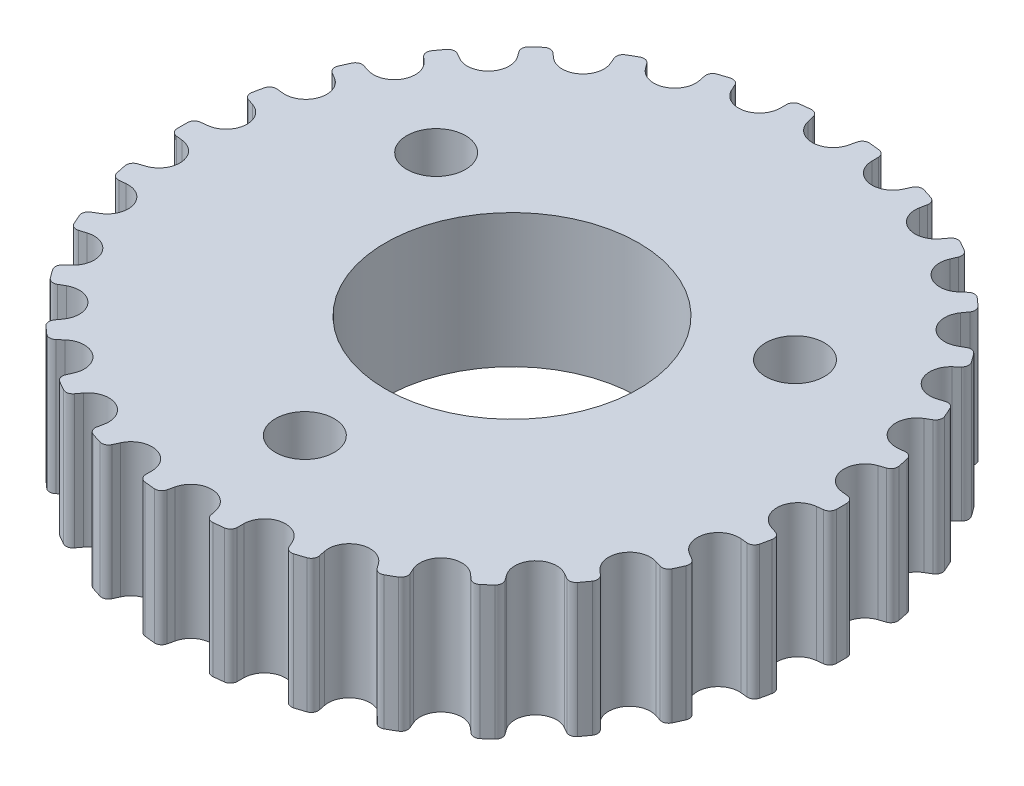
SolidWorks part; units mm, degrees
ref_plane "Front Plane" through (0, 0, 0) normal (0, 0, 1) x (1, 0, 0)
ref_plane "Top Plane" through (0, 0, 0) normal (0, 1, 0) x (1, 0, 0)
ref_plane "Right Plane" through (0, 0, 0) normal (1, 0, 0) x (0, 0, -1)
sketch "Sketch1" plane through (0, 0, 0) normal (0, 1, 0) x (1, 0, 0)
  circle A0 centre (0, 0) radius 14.3239
  dimension "D1" = 28.6479
extrude "Boss-Extrude1" add sketch "Sketch1" along normal blind 5.8
sketch "Sketch2" plane through (0, 5.8, 0) normal (0, 1, 0) x (1, 0, 0)
  line L0 (0, 0) -> (0, 14.3239) construction
  line L1 (-0.8883, 13.7564) -> (-0.95, 14.0339)
  line L2 (-2.9781, 14.0109) -> (-2.9781, 14.3239)
  line L3 (-2.9781, 14.3239) -> (2.9781, 14.3239)
  line L4 (0.8883, 13.7564) -> (0.95, 14.0339)
  line L5 (2.9781, 14.0109) -> (2.9781, 14.3239)
  circle A0 centre (0, 0) radius 14.3239 construction
  arc A1 (0.8883, 13.7564) -> (-0.8883, 13.7564) centre (0, 13.9539) cw
  arc A2 (-0.95, 14.0339) -> (-1.2694, 14.2676) centre (-1.2428, 13.9688) ccw
  arc A4 (0.95, 14.0339) -> (1.2694, 14.2676) centre (1.2428, 13.9688) cw
  arc A5 (-1.2694, 14.2676) -> (-2.9781, 14.0109) centre (0, 0) ccw
  arc A6 (1.2694, 14.2676) -> (2.9781, 14.0109) centre (0, 0) cw
  circle A8 centre (0, 0) radius 14.3239 construction
  point P11 (0, 14.3239)
  point P19 (0, 13.0439)
  dimension "D3" = 0.3
  dimension "D5" = 0.91
  dimension "D2" = 0.95
  dimension "D4" = 1.28
  dimension "D6" = 12
extrude "Cut-Extrude1" cut sketch "Sketch2" against normal through all
pattern_circular "CirPattern1" count 30 over 360 about axis through (0, 0, 0) along (0, 1, 0) of "Cut-Extrude1"
sketch "Sketch3" plane through (0, 0, 0) normal (0, -1, 0) x (1, 0, 0)
  circle A0 centre (0, 0) radius 5.5
  dimension "D1" = 11
extrude "Cut-Extrude2" cut sketch "Sketch3" against normal through all
sketch "Sketch4" plane through (0, 0, 0) normal (0, -1, 0) x (1, 0, 0)
  line L0 (0, 0) -> (0, 9) construction
  circle A0 centre (0, 9) radius 1.275
  circle A1 centre (7.7942, -4.5) radius 1.275
  circle A2 centre (-7.7942, -4.5) radius 1.275
  point P14 (0, 0)
  dimension "D1" = 2.55
  dimension "D2" = 9
  dimension "D3" = 3
extrude "Cut-Extrude3" cut sketch "Sketch4" against normal through all
sketch "Sketch5" plane through (0, 0, 0) normal (0, -1, 0) x (1, 0, 0)
  line L60 (8.7383, -10.682) -> (8.9513, -10.8702)
  line L61 (8.7383, -10.682) -> (8.9513, -10.8702)
  line L62 (9.875, -10.0385) -> (9.7101, -9.807)
  line L63 (9.875, -10.0385) -> (9.7101, -9.807)
  line L64 (12.5987, 6.2896) -> (12.3276, 6.2043)
  line L65 (12.5987, 6.2896) -> (12.3276, 6.2043)
  line L66 (11.5369, 7.5738) -> (11.7463, 7.766)
  line L67 (11.5369, 7.5738) -> (11.7463, 7.766)
  line L68 (-3.638, 13.3126) -> (-3.7561, 13.5712)
  line L69 (-3.638, 13.3126) -> (-3.7561, 13.5712)
  line L70 (-4.9382, 13.1871) -> (-4.8817, 12.9085)
  line L71 (-4.9382, 13.1871) -> (-4.8817, 12.9085)
  line L72 (-11.7463, 7.766) -> (-11.5369, 7.5738)
  line L73 (-11.7463, 7.766) -> (-11.5369, 7.5738)
  line L74 (-12.3276, 6.2043) -> (-12.5987, 6.2896)
  line L75 (-12.3276, 6.2043) -> (-12.5987, 6.2896)
  line L76 (-13.1043, 5.1541) -> (-12.8594, 5.0097)
  line L77 (-13.1043, 5.1541) -> (-12.8594, 5.0097)
  line L78 (-13.3481, 3.5057) -> (-13.6311, 3.5327)
  line L79 (-13.3481, 3.5057) -> (-13.6311, 3.5327)
  line L80 (-13.8895, 2.3169) -> (-13.62, 2.2266)
  line L81 (-13.8895, 2.3169) -> (-13.62, 2.2266)
  line L82 (-13.7853, 0.6538) -> (-14.0677, 0.6215)
  line L83 (-13.7853, 0.6538) -> (-14.0677, 0.6215)
  line L84 (-14.0677, -0.6215) -> (-13.7853, -0.6538)
  line L85 (-14.0677, -0.6215) -> (-13.7853, -0.6538)
  line L86 (-13.62, -2.2266) -> (-13.8895, -2.3169)
  line L87 (-13.62, -2.2266) -> (-13.8895, -2.3169)
  line L88 (-13.6311, -3.5327) -> (-13.3481, -3.5057)
  line L89 (-13.6311, -3.5327) -> (-13.3481, -3.5057)
  line L90 (-12.8594, -5.0097) -> (-13.1043, -5.1541)
  line L91 (-12.8594, -5.0097) -> (-13.1043, -5.1541)
  line L92 (-12.5987, -6.2896) -> (-12.3276, -6.2043)
  line L93 (-12.5987, -6.2896) -> (-12.3276, -6.2043)
  line L94 (-11.5369, -7.5738) -> (-11.7463, -7.766)
  line L95 (-11.5369, -7.5738) -> (-11.7463, -7.766)
  line L96 (-11.0157, -8.7716) -> (-10.7682, -8.6318)
  line L97 (-11.0157, -8.7716) -> (-10.7682, -8.6318)
  line L98 (-9.7101, -9.807) -> (-9.875, -10.0385)
  line L99 (-9.7101, -9.807) -> (-9.875, -10.0385)
  line L100 (-8.9513, -10.8702) -> (-8.7383, -10.682)
  line L101 (-8.9513, -10.8702) -> (-8.7383, -10.682)
  line L102 (-7.4589, -11.6115) -> (-7.5721, -11.8722)
  line L103 (-7.4589, -11.6115) -> (-7.5721, -11.8722)
  line L104 (-6.4956, -12.4937) -> (-6.3264, -12.2653)
  line L105 (-6.4956, -12.4937) -> (-6.3264, -12.2653)
  line L106 (-4.8817, -12.9085) -> (-4.9382, -13.1871)
  line L107 (-4.8817, -12.9085) -> (-4.9382, -13.1871)
  line L108 (-3.7561, -13.5712) -> (-3.638, -13.3126)
  line L109 (-3.7561, -13.5712) -> (-3.638, -13.3126)
  line L110 (-2.0912, -13.6414) -> (-2.0886, -13.9257)
  line L111 (-2.0912, -13.6414) -> (-2.0886, -13.9257)
  line L120 (6.3264, -12.2653) -> (6.4956, -12.4937)
  line L121 (7.5721, -11.8722) -> (7.4589, -11.6115)
  line L124 (10.7682, -8.6318) -> (11.0157, -8.7716)
  line L125 (11.7463, -7.766) -> (11.5369, -7.5738)
  line L126 (12.3276, -6.2043) -> (12.5987, -6.2896)
  line L127 (13.1043, -5.1541) -> (12.8594, -5.0097)
  line L128 (13.3481, -3.5057) -> (13.6311, -3.5327)
  line L129 (13.8895, -2.3169) -> (13.62, -2.2266)
  line L130 (13.7853, -0.6538) -> (14.0677, -0.6215)
  line L131 (14.0677, 0.6215) -> (13.7853, 0.6538)
  line L132 (13.62, 2.2266) -> (13.8895, 2.3169)
  line L133 (13.6311, 3.5327) -> (13.3481, 3.5057)
  line L134 (12.8594, 5.0097) -> (13.1043, 5.1541)
  line L137 (11.0157, 8.7716) -> (10.7682, 8.6318)
  line L138 (9.7101, 9.807) -> (9.875, 10.0385)
  line L139 (8.9513, 10.8702) -> (8.7383, 10.682)
  line L140 (7.4589, 11.6115) -> (7.5721, 11.8722)
  line L141 (6.4956, 12.4937) -> (6.3264, 12.2653)
  line L142 (4.8817, 12.9085) -> (4.9382, 13.1871)
  line L143 (3.7561, 13.5712) -> (3.638, 13.3126)
  line L144 (2.0912, 13.6414) -> (2.0886, 13.9257)
  line L145 (0.8524, 14.0556) -> (0.7907, 13.7781)
  line L146 (-0.7907, 13.7781) -> (-0.8524, 14.0556)
  line L147 (-2.0886, 13.9257) -> (-2.0912, 13.6414)
  line L150 (-6.3264, 12.2653) -> (-6.4956, 12.4937)
  line L151 (-7.5721, 11.8722) -> (-7.4589, 11.6115)
  line L152 (-8.7383, 10.682) -> (-8.9513, 10.8702)
  line L153 (-9.875, 10.0385) -> (-9.7101, 9.807)
  line L154 (-10.7682, 8.6318) -> (-11.0157, 8.7716)
  line L175 (-0.8524, -14.0556) -> (-0.7907, -13.7781)
  line L176 (0.7907, -13.7781) -> (0.8524, -14.0556)
  line L177 (2.0886, -13.9257) -> (2.0912, -13.6414)
  line L178 (3.638, -13.3126) -> (3.7561, -13.5712)
  line L179 (4.9382, -13.1871) -> (4.8817, -12.9085)
  line L180 (6.3264, -12.2653) -> (6.4956, -12.4937)
  line L181 (7.5721, -11.8722) -> (7.4589, -11.6115)
  line L184 (10.7682, -8.6318) -> (11.0157, -8.7716)
  line L185 (11.7463, -7.766) -> (11.5369, -7.5738)
  line L186 (12.3276, -6.2043) -> (12.5987, -6.2896)
  line L187 (13.1043, -5.1541) -> (12.8594, -5.0097)
  line L188 (13.3481, -3.5057) -> (13.6311, -3.5327)
  line L189 (13.8895, -2.3169) -> (13.62, -2.2266)
  line L190 (13.7853, -0.6538) -> (14.0677, -0.6215)
  line L191 (14.0677, 0.6215) -> (13.7853, 0.6538)
  line L192 (13.62, 2.2266) -> (13.8895, 2.3169)
  line L193 (13.6311, 3.5327) -> (13.3481, 3.5057)
  line L194 (12.8594, 5.0097) -> (13.1043, 5.1541)
  line L197 (11.0157, 8.7716) -> (10.7682, 8.6318)
  line L198 (9.7101, 9.807) -> (9.875, 10.0385)
  line L199 (8.9513, 10.8702) -> (8.7383, 10.682)
  line L200 (7.4589, 11.6115) -> (7.5721, 11.8722)
  line L201 (6.4956, 12.4937) -> (6.3264, 12.2653)
  line L202 (4.8817, 12.9085) -> (4.9382, 13.1871)
  line L203 (3.7561, 13.5712) -> (3.638, 13.3126)
  line L204 (2.0912, 13.6414) -> (2.0886, 13.9257)
  line L205 (0.8524, 14.0556) -> (0.7907, 13.7781)
  line L206 (-0.7907, 13.7781) -> (-0.8524, 14.0556)
  line L207 (-2.0886, 13.9257) -> (-2.0912, 13.6414)
  line L210 (-6.3264, 12.2653) -> (-6.4956, 12.4937)
  line L211 (-7.5721, 11.8722) -> (-7.4589, 11.6115)
  line L212 (-8.7383, 10.682) -> (-8.9513, 10.8702)
  line L213 (-9.875, 10.0385) -> (-9.7101, 9.807)
  line L214 (-10.7682, 8.6318) -> (-11.0157, 8.7716)
  line L235 (-0.8524, -14.0556) -> (-0.7907, -13.7781)
  line L236 (0.7907, -13.7781) -> (0.8524, -14.0556)
  line L237 (2.0886, -13.9257) -> (2.0912, -13.6414)
  line L238 (3.638, -13.3126) -> (3.7561, -13.5712)
  line L239 (4.9382, -13.1871) -> (4.8817, -12.9085)
  arc A76 (8.9513, -10.8702) -> (9.479, -10.8719) centre (9.2161, -10.5704) ccw
  arc A77 (8.9513, -10.8702) -> (9.479, -10.8719) centre (9.2161, -10.5704) ccw
  arc A78 (9.479, -10.8719) -> (9.8216, -10.5635) centre (0, 0) ccw
  arc A79 (9.479, -10.8719) -> (9.8216, -10.5635) centre (0, 0) ccw
  arc A80 (9.8216, -10.5635) -> (9.875, -10.0385) centre (9.5492, -10.2705) ccw
  arc A81 (9.8216, -10.5635) -> (9.875, -10.0385) centre (9.5492, -10.2705) ccw
  circle A120 centre (0, 0) radius 13.0439
  arc A121 (-0.8883, 13.7564) -> (0.8883, 13.7564) centre (0, 13.9539) ccw construction
  arc A128 (11.5369, 7.5738) -> (12.3276, 6.2043) centre (12.0845, 6.977) ccw
  arc A129 (11.5369, 7.5738) -> (12.3276, 6.2043) centre (12.0845, 6.977) ccw
  arc A130 (-3.7561, 13.5712) -> (-4.2375, 13.7875) centre (-4.12, 13.4051) ccw
  arc A131 (-3.7561, 13.5712) -> (-4.2375, 13.7875) centre (-4.12, 13.4051) ccw
  arc A132 (-4.2375, 13.7875) -> (-4.6759, 13.645) centre (0, 0) ccw
  arc A133 (-4.2375, 13.7875) -> (-4.6759, 13.645) centre (0, 0) ccw
  arc A134 (-4.6759, 13.645) -> (-4.9382, 13.1871) centre (-4.5462, 13.2666) ccw
  arc A135 (-4.6759, 13.645) -> (-4.9382, 13.1871) centre (-4.5462, 13.2666) ccw
  arc A136 (-11.8032, 8.2906) -> (-11.7463, 7.766) centre (-11.4759, 8.0607) ccw
  arc A137 (-11.8032, 8.2906) -> (-11.7463, 7.766) centre (-11.4759, 8.0607) ccw
  arc A138 (-12.3276, 6.2043) -> (-11.5369, 7.5738) centre (-12.0845, 6.977) ccw
  arc A139 (-12.3276, 6.2043) -> (-11.5369, 7.5738) centre (-12.0845, 6.977) ccw
  arc A140 (-12.5987, 6.2896) -> (-13.0815, 6.0766) centre (-12.7187, 5.908) ccw
  arc A141 (-12.5987, 6.2896) -> (-13.0815, 6.0766) centre (-12.7187, 5.908) ccw
  arc A142 (-13.0815, 6.0766) -> (-13.269, 5.6554) centre (0, 0) ccw
  arc A143 (-13.0815, 6.0766) -> (-13.269, 5.6554) centre (0, 0) ccw
  arc A144 (-13.269, 5.6554) -> (-13.1043, 5.1541) centre (-12.901, 5.4986) ccw
  arc A145 (-13.269, 5.6554) -> (-13.1043, 5.1541) centre (-12.901, 5.4986) ccw
  arc A146 (-13.3481, 3.5057) -> (-12.8594, 5.0097) centre (-13.271, 4.312) ccw
  arc A147 (-13.3481, 3.5057) -> (-12.8594, 5.0097) centre (-13.271, 4.312) ccw
  arc A148 (-13.6311, 3.5327) -> (-14.059, 3.224) centre (-13.6691, 3.1346) ccw
  arc A149 (-13.6311, 3.5327) -> (-14.059, 3.224) centre (-13.6691, 3.1346) ccw
  arc A150 (-14.059, 3.224) -> (-14.1549, 2.7731) centre (0, 0) ccw
  arc A151 (-14.059, 3.224) -> (-14.1549, 2.7731) centre (0, 0) ccw
  arc A152 (-14.1549, 2.7731) -> (-13.8895, 2.3169) centre (-13.7623, 2.6962) ccw
  arc A153 (-14.1549, 2.7731) -> (-13.8895, 2.3169) centre (-13.7623, 2.6962) ccw
  arc A154 (-13.7853, 0.6538) -> (-13.62, 2.2266) centre (-13.8775, 1.4586) ccw
  arc A155 (-13.7853, 0.6538) -> (-13.62, 2.2266) centre (-13.8775, 1.4586) ccw
  arc A156 (-14.0677, 0.6215) -> (-14.4221, 0.2305) centre (-14.0222, 0.2241) ccw
  arc A157 (-14.0677, 0.6215) -> (-14.4221, 0.2305) centre (-14.0222, 0.2241) ccw
  arc A158 (-14.4221, 0.2305) -> (-14.4221, -0.2305) centre (0, 0) ccw
  arc A159 (-14.4221, 0.2305) -> (-14.4221, -0.2305) centre (0, 0) ccw
  arc A160 (-14.4221, -0.2305) -> (-14.0677, -0.6215) centre (-14.0222, -0.2241) ccw
  arc A161 (-14.4221, -0.2305) -> (-14.0677, -0.6215) centre (-14.0222, -0.2241) ccw
  arc A162 (-13.62, -2.2266) -> (-13.7853, -0.6538) centre (-13.8775, -1.4586) ccw
  arc A163 (-13.62, -2.2266) -> (-13.7853, -0.6538) centre (-13.8775, -1.4586) ccw
  arc A164 (-13.8895, -2.3169) -> (-14.1549, -2.7731) centre (-13.7623, -2.6962) ccw
  arc A165 (-13.8895, -2.3169) -> (-14.1549, -2.7731) centre (-13.7623, -2.6962) ccw
  arc A166 (-14.1549, -2.7731) -> (-14.059, -3.224) centre (0, 0) ccw
  arc A167 (-14.1549, -2.7731) -> (-14.059, -3.224) centre (0, 0) ccw
  arc A168 (-14.059, -3.224) -> (-13.6311, -3.5327) centre (-13.6691, -3.1346) ccw
  arc A169 (-14.059, -3.224) -> (-13.6311, -3.5327) centre (-13.6691, -3.1346) ccw
  arc A170 (-12.8594, -5.0097) -> (-13.3481, -3.5057) centre (-13.271, -4.312) ccw
  arc A171 (-12.8594, -5.0097) -> (-13.3481, -3.5057) centre (-13.271, -4.312) ccw
  arc A172 (-13.1043, -5.1541) -> (-13.269, -5.6554) centre (-12.901, -5.4986) ccw
  arc A173 (-13.1043, -5.1541) -> (-13.269, -5.6554) centre (-12.901, -5.4986) ccw
  arc A174 (-13.269, -5.6554) -> (-13.0815, -6.0766) centre (0, 0) ccw
  arc A175 (-13.269, -5.6554) -> (-13.0815, -6.0766) centre (0, 0) ccw
  arc A176 (-13.0815, -6.0766) -> (-12.5987, -6.2896) centre (-12.7187, -5.908) ccw
  arc A177 (-13.0815, -6.0766) -> (-12.5987, -6.2896) centre (-12.7187, -5.908) ccw
  arc A178 (-11.5369, -7.5738) -> (-12.3276, -6.2043) centre (-12.0845, -6.977) ccw
  arc A179 (-11.5369, -7.5738) -> (-12.3276, -6.2043) centre (-12.0845, -6.977) ccw
  arc A180 (-11.7463, -7.766) -> (-11.8032, -8.2906) centre (-11.4759, -8.0607) ccw
  arc A181 (-11.7463, -7.766) -> (-11.8032, -8.2906) centre (-11.4759, -8.0607) ccw
  arc A182 (-11.8032, -8.2906) -> (-11.5323, -8.6636) centre (0, 0) ccw
  arc A183 (-11.8032, -8.2906) -> (-11.5323, -8.6636) centre (0, 0) ccw
  arc A184 (-11.5323, -8.6636) -> (-11.0157, -8.7716) centre (-11.2124, -8.4233) ccw
  arc A185 (-11.5323, -8.6636) -> (-11.0157, -8.7716) centre (-11.2124, -8.4233) ccw
  arc A186 (-9.7101, -9.807) -> (-10.7682, -8.6318) centre (-10.3698, -9.337) ccw
  arc A187 (-9.7101, -9.807) -> (-10.7682, -8.6318) centre (-10.3698, -9.337) ccw
  arc A188 (-9.875, -10.0385) -> (-9.8216, -10.5635) centre (-9.5492, -10.2705) ccw
  arc A189 (-9.875, -10.0385) -> (-9.8216, -10.5635) centre (-9.5492, -10.2705) ccw
  arc A190 (-9.8216, -10.5635) -> (-9.479, -10.8719) centre (0, 0) ccw
  arc A191 (-9.8216, -10.5635) -> (-9.479, -10.8719) centre (0, 0) ccw
  arc A192 (-9.479, -10.8719) -> (-8.9513, -10.8702) centre (-9.2161, -10.5704) ccw
  arc A193 (-9.479, -10.8719) -> (-8.9513, -10.8702) centre (-9.2161, -10.5704) ccw
  arc A194 (-7.4589, -11.6115) -> (-8.7383, -10.682) centre (-8.2019, -11.289) ccw
  arc A195 (-7.4589, -11.6115) -> (-8.7383, -10.682) centre (-8.2019, -11.289) ccw
  arc A196 (-7.5721, -11.8722) -> (-7.4107, -12.3747) centre (-7.2051, -12.0315) ccw
  arc A197 (-7.5721, -11.8722) -> (-7.4107, -12.3747) centre (-7.2051, -12.0315) ccw
  arc A198 (-7.4107, -12.3747) -> (-7.0114, -12.6052) centre (0, 0) ccw
  arc A199 (-7.4107, -12.3747) -> (-7.0114, -12.6052) centre (0, 0) ccw
  arc A200 (-7.0114, -12.6052) -> (-6.4956, -12.4937) centre (-6.817, -12.2556) ccw
  arc A201 (-7.0114, -12.6052) -> (-6.4956, -12.4937) centre (-6.817, -12.2556) ccw
  arc A202 (-4.8817, -12.9085) -> (-6.3264, -12.2653) centre (-5.6756, -12.7476) ccw
  arc A203 (-4.8817, -12.9085) -> (-6.3264, -12.2653) centre (-5.6756, -12.7476) ccw
  arc A204 (-4.9382, -13.1871) -> (-4.6759, -13.645) centre (-4.5462, -13.2666) ccw
  arc A205 (-4.9382, -13.1871) -> (-4.6759, -13.645) centre (-4.5462, -13.2666) ccw
  arc A206 (-4.6759, -13.645) -> (-4.2375, -13.7875) centre (0, 0) ccw
  arc A207 (-4.6759, -13.645) -> (-4.2375, -13.7875) centre (0, 0) ccw
  arc A208 (-4.2375, -13.7875) -> (-3.7561, -13.5712) centre (-4.12, -13.4051) ccw
  arc A209 (-4.2375, -13.7875) -> (-3.7561, -13.5712) centre (-4.12, -13.4051) ccw
  arc A210 (-2.0912, -13.6414) -> (-3.638, -13.3126) centre (-2.9012, -13.649) ccw
  arc A211 (-2.0912, -13.6414) -> (-3.638, -13.3126) centre (-2.9012, -13.649) ccw
  arc A212 (-2.0886, -13.9257) -> (-1.7367, -14.319) centre (-1.6886, -13.9219) ccw
  arc A213 (-2.0886, -13.9257) -> (-1.7367, -14.319) centre (-1.6886, -13.9219) ccw
  arc A214 (-1.7367, -14.319) -> (-1.2783, -14.3672) centre (0, 0) ccw
  arc A215 (-1.7367, -14.319) -> (-1.2783, -14.3672) centre (0, 0) ccw
  arc A240 (6.4956, -12.4937) -> (7.0114, -12.6052) centre (6.817, -12.2556) ccw
  arc A241 (7.0114, -12.6052) -> (7.4107, -12.3747) centre (0, 0) ccw
  arc A242 (7.4107, -12.3747) -> (7.5721, -11.8722) centre (7.2051, -12.0315) ccw
  arc A243 (8.7383, -10.682) -> (7.4589, -11.6115) centre (8.2019, -11.289) ccw
  arc A247 (10.7682, -8.6318) -> (9.7101, -9.807) centre (10.3698, -9.337) ccw
  arc A248 (11.0157, -8.7716) -> (11.5323, -8.6636) centre (11.2124, -8.4233) ccw
  arc A249 (11.5323, -8.6636) -> (11.8032, -8.2906) centre (0, 0) ccw
  arc A250 (11.8032, -8.2906) -> (11.7463, -7.766) centre (11.4759, -8.0607) ccw
  arc A251 (12.3276, -6.2043) -> (11.5369, -7.5738) centre (12.0845, -6.977) ccw
  arc A252 (12.5987, -6.2896) -> (13.0815, -6.0766) centre (12.7187, -5.908) ccw
  arc A253 (13.0815, -6.0766) -> (13.269, -5.6554) centre (0, 0) ccw
  arc A254 (13.269, -5.6554) -> (13.1043, -5.1541) centre (12.901, -5.4986) ccw
  arc A255 (13.3481, -3.5057) -> (12.8594, -5.0097) centre (13.271, -4.312) ccw
  arc A256 (13.6311, -3.5327) -> (14.059, -3.224) centre (13.6691, -3.1346) ccw
  arc A257 (14.059, -3.224) -> (14.1549, -2.7731) centre (0, 0) ccw
  arc A258 (14.1549, -2.7731) -> (13.8895, -2.3169) centre (13.7623, -2.6962) ccw
  arc A259 (13.7853, -0.6538) -> (13.62, -2.2266) centre (13.8775, -1.4586) ccw
  arc A260 (14.0677, -0.6215) -> (14.4221, -0.2305) centre (14.0222, -0.2241) ccw
  arc A261 (14.4221, -0.2305) -> (14.4221, 0.2305) centre (0, 0) ccw
  arc A262 (14.4221, 0.2305) -> (14.0677, 0.6215) centre (14.0222, 0.2241) ccw
  arc A263 (13.62, 2.2266) -> (13.7853, 0.6538) centre (13.8775, 1.4586) ccw
  arc A264 (13.8895, 2.3169) -> (14.1549, 2.7731) centre (13.7623, 2.6962) ccw
  arc A265 (14.1549, 2.7731) -> (14.059, 3.224) centre (0, 0) ccw
  arc A266 (14.059, 3.224) -> (13.6311, 3.5327) centre (13.6691, 3.1346) ccw
  arc A267 (12.8594, 5.0097) -> (13.3481, 3.5057) centre (13.271, 4.312) ccw
  arc A268 (13.1043, 5.1541) -> (13.269, 5.6554) centre (12.901, 5.4986) ccw
  arc A269 (13.269, 5.6554) -> (13.0815, 6.0766) centre (0, 0) ccw
  arc A270 (13.0815, 6.0766) -> (12.5987, 6.2896) centre (12.7187, 5.908) ccw
  arc A272 (11.7463, 7.766) -> (11.8032, 8.2906) centre (11.4759, 8.0607) ccw
  arc A273 (11.8032, 8.2906) -> (11.5323, 8.6636) centre (0, 0) ccw
  arc A274 (11.5323, 8.6636) -> (11.0157, 8.7716) centre (11.2124, 8.4233) ccw
  arc A275 (9.7101, 9.807) -> (10.7682, 8.6318) centre (10.3698, 9.337) ccw
  arc A276 (9.875, 10.0385) -> (9.8216, 10.5635) centre (9.5492, 10.2705) ccw
  arc A277 (9.8216, 10.5635) -> (9.479, 10.8719) centre (0, 0) ccw
  arc A278 (9.479, 10.8719) -> (8.9513, 10.8702) centre (9.2161, 10.5704) ccw
  arc A279 (7.4589, 11.6115) -> (8.7383, 10.682) centre (8.2019, 11.289) ccw
  arc A280 (7.5721, 11.8722) -> (7.4107, 12.3747) centre (7.2051, 12.0315) ccw
  arc A281 (7.4107, 12.3747) -> (7.0114, 12.6052) centre (0, 0) ccw
  arc A282 (7.0114, 12.6052) -> (6.4956, 12.4937) centre (6.817, 12.2556) ccw
  arc A283 (4.8817, 12.9085) -> (6.3264, 12.2653) centre (5.6756, 12.7476) ccw
  arc A284 (4.9382, 13.1871) -> (4.6759, 13.645) centre (4.5462, 13.2666) ccw
  arc A285 (4.6759, 13.645) -> (4.2375, 13.7875) centre (0, 0) ccw
  arc A286 (4.2375, 13.7875) -> (3.7561, 13.5712) centre (4.12, 13.4051) ccw
  arc A287 (2.0912, 13.6414) -> (3.638, 13.3126) centre (2.9012, 13.649) ccw
  arc A288 (2.0886, 13.9257) -> (1.7367, 14.319) centre (1.6886, 13.9219) ccw
  arc A289 (1.7367, 14.319) -> (1.2783, 14.3672) centre (0, 0) ccw
  arc A290 (1.2783, 14.3672) -> (0.8524, 14.0556) centre (1.2428, 13.9688) ccw
  arc A291 (-0.7907, 13.7781) -> (0.7907, 13.7781) centre (0, 13.9539) ccw
  arc A292 (-0.8524, 14.0556) -> (-1.2783, 14.3672) centre (-1.2428, 13.9688) ccw
  arc A293 (-1.2783, 14.3672) -> (-1.7367, 14.319) centre (0, 0) ccw
  arc A294 (-1.7367, 14.319) -> (-2.0886, 13.9257) centre (-1.6886, 13.9219) ccw
  arc A295 (-3.638, 13.3126) -> (-2.0912, 13.6414) centre (-2.9012, 13.649) ccw
  arc A299 (-6.3264, 12.2653) -> (-4.8817, 12.9085) centre (-5.6756, 12.7476) ccw
  arc A300 (-6.4956, 12.4937) -> (-7.0114, 12.6052) centre (-6.817, 12.2556) ccw
  arc A301 (-7.0114, 12.6052) -> (-7.4107, 12.3747) centre (0, 0) ccw
  arc A302 (-7.4107, 12.3747) -> (-7.5721, 11.8722) centre (-7.2051, 12.0315) ccw
  arc A303 (-8.7383, 10.682) -> (-7.4589, 11.6115) centre (-8.2019, 11.289) ccw
  arc A304 (-8.9513, 10.8702) -> (-9.479, 10.8719) centre (-9.2161, 10.5704) ccw
  arc A305 (-9.479, 10.8719) -> (-9.8216, 10.5635) centre (0, 0) ccw
  arc A306 (-9.8216, 10.5635) -> (-9.875, 10.0385) centre (-9.5492, 10.2705) ccw
  arc A307 (-10.7682, 8.6318) -> (-9.7101, 9.807) centre (-10.3698, 9.337) ccw
  arc A308 (-11.0157, 8.7716) -> (-11.5323, 8.6636) centre (-11.2124, 8.4233) ccw
  arc A309 (-11.5323, 8.6636) -> (-11.8032, 8.2906) centre (0, 0) ccw
  arc A350 (-1.2783, -14.3672) -> (-0.8524, -14.0556) centre (-1.2428, -13.9688) ccw
  arc A351 (0.7907, -13.7781) -> (-0.7907, -13.7781) centre (0, -13.9539) ccw
  arc A352 (0.8524, -14.0556) -> (1.2783, -14.3672) centre (1.2428, -13.9688) ccw
  arc A353 (1.2783, -14.3672) -> (1.7367, -14.319) centre (0, 0) ccw
  arc A354 (1.7367, -14.319) -> (2.0886, -13.9257) centre (1.6886, -13.9219) ccw
  arc A355 (3.638, -13.3126) -> (2.0912, -13.6414) centre (2.9012, -13.649) ccw
  arc A356 (3.7561, -13.5712) -> (4.2375, -13.7875) centre (4.12, -13.4051) ccw
  arc A357 (4.2375, -13.7875) -> (4.6759, -13.645) centre (0, 0) ccw
  arc A358 (4.6759, -13.645) -> (4.9382, -13.1871) centre (4.5462, -13.2666) ccw
  arc A359 (6.3264, -12.2653) -> (4.8817, -12.9085) centre (5.6756, -12.7476) ccw
  arc A360 (6.4956, -12.4937) -> (7.0114, -12.6052) centre (6.817, -12.2556) ccw
  arc A361 (7.0114, -12.6052) -> (7.4107, -12.3747) centre (0, 0) ccw
  arc A362 (7.4107, -12.3747) -> (7.5721, -11.8722) centre (7.2051, -12.0315) ccw
  arc A363 (8.7383, -10.682) -> (7.4589, -11.6115) centre (8.2019, -11.289) ccw
  arc A367 (10.7682, -8.6318) -> (9.7101, -9.807) centre (10.3698, -9.337) ccw
  arc A368 (11.0157, -8.7716) -> (11.5323, -8.6636) centre (11.2124, -8.4233) ccw
  arc A369 (11.5323, -8.6636) -> (11.8032, -8.2906) centre (0, 0) ccw
  arc A370 (11.8032, -8.2906) -> (11.7463, -7.766) centre (11.4759, -8.0607) ccw
  arc A371 (12.3276, -6.2043) -> (11.5369, -7.5738) centre (12.0845, -6.977) ccw
  arc A372 (12.5987, -6.2896) -> (13.0815, -6.0766) centre (12.7187, -5.908) ccw
  arc A373 (13.0815, -6.0766) -> (13.269, -5.6554) centre (0, 0) ccw
  arc A374 (13.269, -5.6554) -> (13.1043, -5.1541) centre (12.901, -5.4986) ccw
  arc A375 (13.3481, -3.5057) -> (12.8594, -5.0097) centre (13.271, -4.312) ccw
  arc A376 (13.6311, -3.5327) -> (14.059, -3.224) centre (13.6691, -3.1346) ccw
  arc A377 (14.059, -3.224) -> (14.1549, -2.7731) centre (0, 0) ccw
  arc A378 (14.1549, -2.7731) -> (13.8895, -2.3169) centre (13.7623, -2.6962) ccw
  arc A379 (13.7853, -0.6538) -> (13.62, -2.2266) centre (13.8775, -1.4586) ccw
  arc A380 (14.0677, -0.6215) -> (14.4221, -0.2305) centre (14.0222, -0.2241) ccw
  arc A381 (14.4221, -0.2305) -> (14.4221, 0.2305) centre (0, 0) ccw
  arc A382 (14.4221, 0.2305) -> (14.0677, 0.6215) centre (14.0222, 0.2241) ccw
  arc A383 (13.62, 2.2266) -> (13.7853, 0.6538) centre (13.8775, 1.4586) ccw
  arc A384 (13.8895, 2.3169) -> (14.1549, 2.7731) centre (13.7623, 2.6962) ccw
  arc A385 (14.1549, 2.7731) -> (14.059, 3.224) centre (0, 0) ccw
  arc A386 (14.059, 3.224) -> (13.6311, 3.5327) centre (13.6691, 3.1346) ccw
  arc A387 (12.8594, 5.0097) -> (13.3481, 3.5057) centre (13.271, 4.312) ccw
  arc A388 (13.1043, 5.1541) -> (13.269, 5.6554) centre (12.901, 5.4986) ccw
  arc A389 (13.269, 5.6554) -> (13.0815, 6.0766) centre (0, 0) ccw
  arc A390 (13.0815, 6.0766) -> (12.5987, 6.2896) centre (12.7187, 5.908) ccw
  arc A392 (11.7463, 7.766) -> (11.8032, 8.2906) centre (11.4759, 8.0607) ccw
  arc A393 (11.8032, 8.2906) -> (11.5323, 8.6636) centre (0, 0) ccw
  arc A394 (11.5323, 8.6636) -> (11.0157, 8.7716) centre (11.2124, 8.4233) ccw
  arc A395 (9.7101, 9.807) -> (10.7682, 8.6318) centre (10.3698, 9.337) ccw
  arc A396 (9.875, 10.0385) -> (9.8216, 10.5635) centre (9.5492, 10.2705) ccw
  arc A397 (9.8216, 10.5635) -> (9.479, 10.8719) centre (0, 0) ccw
  arc A398 (9.479, 10.8719) -> (8.9513, 10.8702) centre (9.2161, 10.5704) ccw
  arc A399 (7.4589, 11.6115) -> (8.7383, 10.682) centre (8.2019, 11.289) ccw
  arc A400 (7.5721, 11.8722) -> (7.4107, 12.3747) centre (7.2051, 12.0315) ccw
  arc A401 (7.4107, 12.3747) -> (7.0114, 12.6052) centre (0, 0) ccw
  arc A402 (7.0114, 12.6052) -> (6.4956, 12.4937) centre (6.817, 12.2556) ccw
  arc A403 (4.8817, 12.9085) -> (6.3264, 12.2653) centre (5.6756, 12.7476) ccw
  arc A404 (4.9382, 13.1871) -> (4.6759, 13.645) centre (4.5462, 13.2666) ccw
  arc A405 (4.6759, 13.645) -> (4.2375, 13.7875) centre (0, 0) ccw
  arc A406 (4.2375, 13.7875) -> (3.7561, 13.5712) centre (4.12, 13.4051) ccw
  arc A407 (2.0912, 13.6414) -> (3.638, 13.3126) centre (2.9012, 13.649) ccw
  arc A408 (2.0886, 13.9257) -> (1.7367, 14.319) centre (1.6886, 13.9219) ccw
  arc A409 (1.7367, 14.319) -> (1.2783, 14.3672) centre (0, 0) ccw
  arc A410 (1.2783, 14.3672) -> (0.8524, 14.0556) centre (1.2428, 13.9688) ccw
  arc A411 (-0.7907, 13.7781) -> (0.7907, 13.7781) centre (0, 13.9539) ccw
  arc A412 (-0.8524, 14.0556) -> (-1.2783, 14.3672) centre (-1.2428, 13.9688) ccw
  arc A413 (-1.2783, 14.3672) -> (-1.7367, 14.319) centre (0, 0) ccw
  arc A414 (-1.7367, 14.319) -> (-2.0886, 13.9257) centre (-1.6886, 13.9219) ccw
  arc A415 (-3.638, 13.3126) -> (-2.0912, 13.6414) centre (-2.9012, 13.649) ccw
  arc A419 (-6.3264, 12.2653) -> (-4.8817, 12.9085) centre (-5.6756, 12.7476) ccw
  arc A420 (-6.4956, 12.4937) -> (-7.0114, 12.6052) centre (-6.817, 12.2556) ccw
  arc A421 (-7.0114, 12.6052) -> (-7.4107, 12.3747) centre (0, 0) ccw
  arc A422 (-7.4107, 12.3747) -> (-7.5721, 11.8722) centre (-7.2051, 12.0315) ccw
  arc A423 (-8.7383, 10.682) -> (-7.4589, 11.6115) centre (-8.2019, 11.289) ccw
  arc A424 (-8.9513, 10.8702) -> (-9.479, 10.8719) centre (-9.2161, 10.5704) ccw
  arc A425 (-9.479, 10.8719) -> (-9.8216, 10.5635) centre (0, 0) ccw
  arc A426 (-9.8216, 10.5635) -> (-9.875, 10.0385) centre (-9.5492, 10.2705) ccw
  arc A427 (-10.7682, 8.6318) -> (-9.7101, 9.807) centre (-10.3698, 9.337) ccw
  arc A428 (-11.0157, 8.7716) -> (-11.5323, 8.6636) centre (-11.2124, 8.4233) ccw
  arc A429 (-11.5323, 8.6636) -> (-11.8032, 8.2906) centre (0, 0) ccw
  arc A470 (-1.2783, -14.3672) -> (-0.8524, -14.0556) centre (-1.2428, -13.9688) ccw
  arc A471 (0.7907, -13.7781) -> (-0.7907, -13.7781) centre (0, -13.9539) ccw
  arc A472 (0.8524, -14.0556) -> (1.2783, -14.3672) centre (1.2428, -13.9688) ccw
  arc A473 (1.2783, -14.3672) -> (1.7367, -14.319) centre (0, 0) ccw
  arc A474 (1.7367, -14.319) -> (2.0886, -13.9257) centre (1.6886, -13.9219) ccw
  arc A475 (3.638, -13.3126) -> (2.0912, -13.6414) centre (2.9012, -13.649) ccw
  arc A476 (3.7561, -13.5712) -> (4.2375, -13.7875) centre (4.12, -13.4051) ccw
  arc A477 (4.2375, -13.7875) -> (4.6759, -13.645) centre (0, 0) ccw
  arc A478 (4.6759, -13.645) -> (4.9382, -13.1871) centre (4.5462, -13.2666) ccw
  arc A479 (6.3264, -12.2653) -> (4.8817, -12.9085) centre (5.6756, -12.7476) ccw
  dimension "D1" = 0.1
extrude "Boss-Extrude2" [suppressed] add sketch "Sketch5" against normal up to surface (5.8 mm away)
equation "\"smallPulleyTeeth\"= 15"
equation "\"largePulleyTeeth\"= 30"
equation "\"eighthThick\"= 2.9mm"
equation "\"D1@Sketch1\"=3*\"largePulleyTeeth\"/pi"
equation "\"D1@Boss-Extrude1\" = \"eighthThick\" * 2"
equation "\"D6@Sketch2\"=360/\"largePulleyTeeth\""
equation "\"quarterThick\"=5.9mm"
equation "\"D1@CirPattern1\"=\"largePulleyTeeth\""
equation "\"sixteenthThick\"= 1.7mm"
equation "\"OD\"= 145mm"
equation "\"puckAngle\"= 60.5deg"
equation "\"puckDiam\"= 76.5mm"
equation "\"axlePress\"= 5.9mm"
equation "\"press\"= 0.2mm"
equation "\"wheelClear\"= 0.3mm"
equation "\"10-32clear\"= 4.5mm"
equation "\"D1@Sketch4\"=\"4-40clear\""
equation "\"6-32clear\"= 3.3mm"
equation "\"8-32clear\"= 4.0mm"
equation "\"4-40clear\"= 2.55mm"
equation "\"wheelHeight\"= 22mm"
equation "\"wheelWell\"= 65mm"
